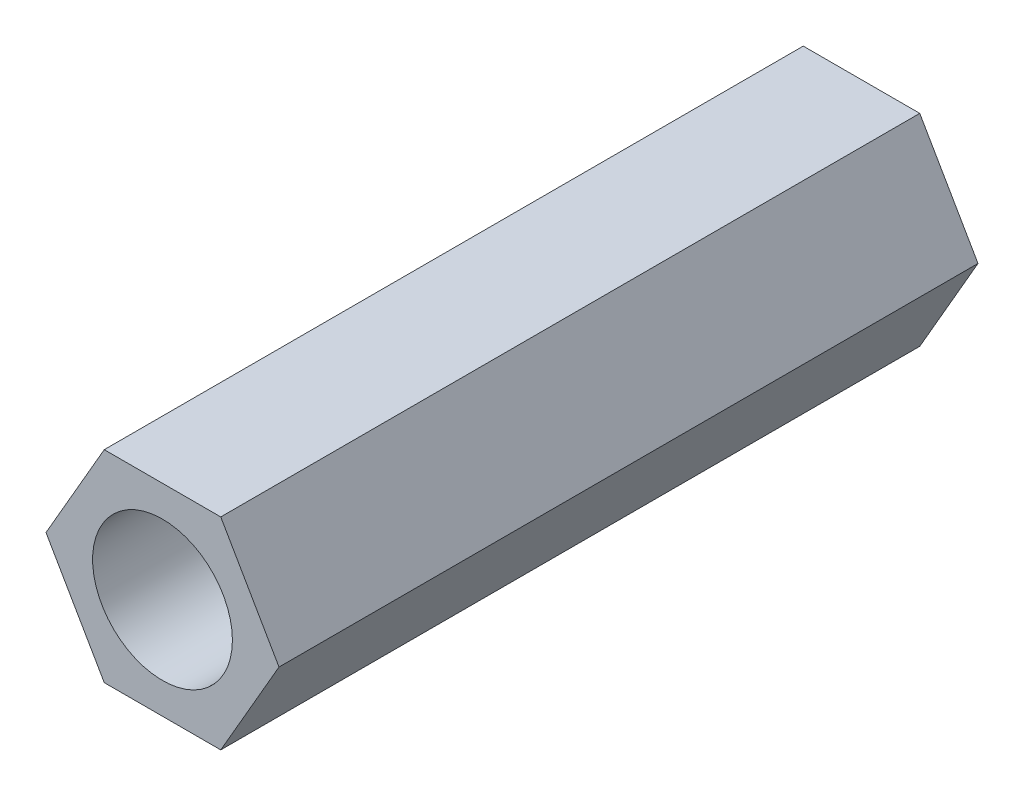
SolidWorks part; units mm, degrees
material "铜"
ref_plane "前视基准面" through (0, 0, 0) normal (0, 0, 1) x (1, 0, 0)
ref_plane "上视基准面" through (0, 0, 0) normal (0, 1, 0) x (1, 0, 0)
ref_plane "右视基准面" through (0, 0, 0) normal (1, 0, 0) x (0, 0, -1)
other "Configuration Table"
sketch "草图1" plane through (0, 0, 0) normal (0, 0, 1) x (1, 0, 0)
  line L1 (2.5, 0) -> (1.25, 2.1651)
  line L2 (1.25, 2.1651) -> (-1.25, 2.1651)
  line L3 (-1.25, 2.1651) -> (-2.5, 0)
  line L4 (-2.5, 0) -> (-1.25, -2.1651)
  line L5 (-1.25, -2.1651) -> (1.25, -2.1651)
  line L6 (1.25, -2.1651) -> (2.5, 0)
  circle A0 centre (0, 0) radius 1.5
  circle A1 centre (0, 0) radius 2.1651 construction
  dimension "D2" = 3
  dimension "D1" = 5
extrude "凸台-拉伸1" add sketch "草图1" along normal blind 15
